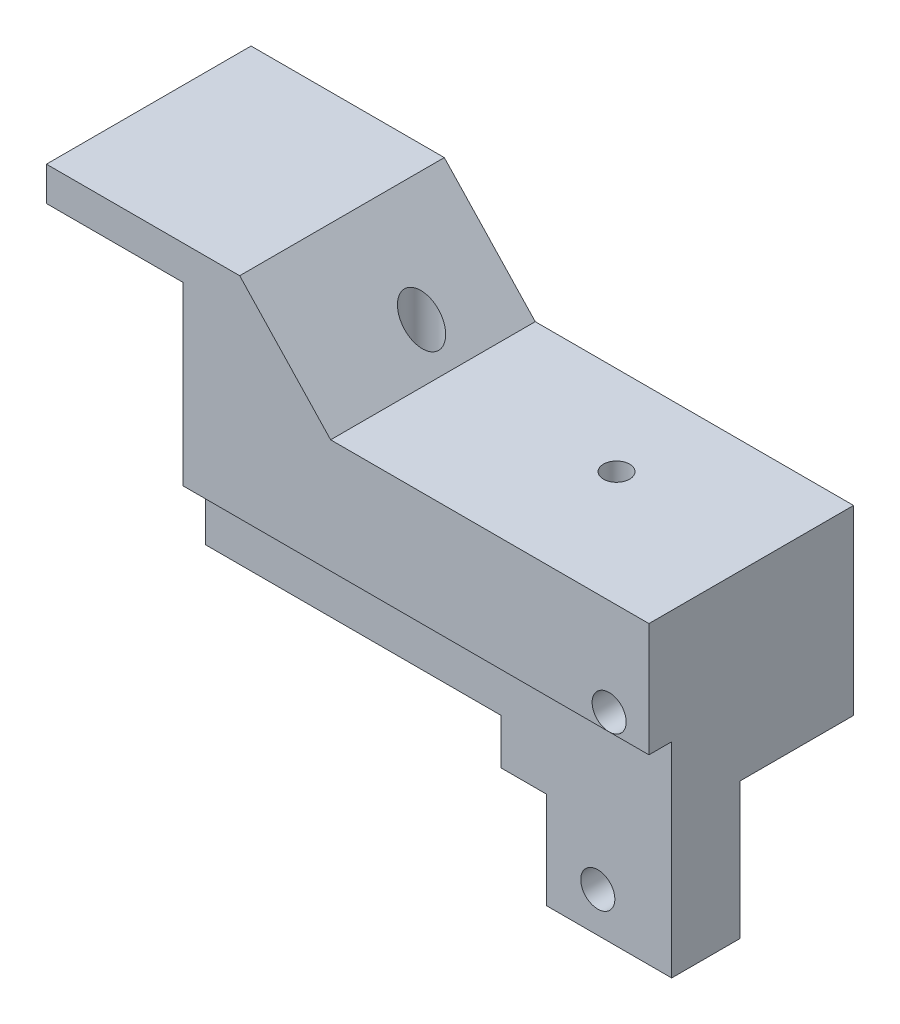
SolidWorks part; units mm, degrees
ref_plane "Front Plane" through (0, 0, 0) normal (0, 0, 1) x (1, 0, 0)
ref_plane "Top Plane" through (0, 0, 0) normal (0, 1, 0) x (1, 0, 0)
ref_plane "Right Plane" through (0, 0, 0) normal (1, 0, 0) x (0, 0, -1)
sketch "Sketch1" plane through (0, 0, 0) normal (0, 0, 1) x (1, 0, 0)
  line L1 (-20.5, -14) -> (20.5, -14)
  line L2 (-20.5, -14) -> (-20.5, 14)
  line L3 (-20.5, 14) -> (20.5, 14)
  line L4 (20.5, -14) -> (20.5, 14)
  line L5 (-20.5, -14) -> (20.5, 14) construction
  line L6 (-20.5, 14) -> (20.5, -14) construction
  point P0 (0, 0)
  dimension "D1" = 41
  dimension "D2" = 28
extrude "Boss-Extrude1" add sketch "Sketch1" along normal blind 18
sketch "Sketch2" plane through (0, 0, 18) normal (0, 0, 1) x (1, 0, 0)
  line L0 (9.5, -14) -> (9.5, -5.5)
  line L1 (-20.5, -14) -> (20.5, -14) construction
  line L2 (9.5, -5.5) -> (5.5, -5.5)
  line L3 (5.5, -5.5) -> (5.5, -1.5)
  line L4 (5.5, -1.5) -> (-20.5, -1.5)
  line L5 (-20.5, 14) -> (-20.5, -14) construction
  line L6 (-20.5, -1.5) -> (-20.5, -14)
  line L7 (-20.5, -14) -> (9.5, -14)
  dimension "D1" = 11
  dimension "D2" = 8.5
  dimension "D3" = 4
extrude "Cut-Extrude1" cut sketch "Sketch2" against normal blind 18
sketch "Sketch3" plane through (0, 0, 18) normal (0, 0, 1) x (1, 0, 0)
  line L0 (-20.5, -1.5) -> (-20.5, 22.5) construction
  line L1 (-20.5, 22.5) -> (-32.5, 22.5)
  line L2 (-32.5, 22.5) -> (-32.5, 19.5)
  line L3 (-32.5, 19.5) -> (-20.5, 19.5)
  line L4 (-20.5, 19.5) -> (-20.5, 14)
  line L7 (20.5, 14) -> (-20.5, 14) construction
  line L8 (-7.5, 14) -> (-20.5, 14)
  line L9 (-20.5, 22.5) -> (-15.5, 22.5)
  line L10 (-15.5, 22.5) -> (-7.5, 14)
  dimension "D1" = 24
  dimension "D2" = 12
  dimension "D3" = 3
  dimension "D4" = 13
  dimension "D5" = 5
extrude "Boss-Extrude2" add sketch "Sketch3" against normal up to surface (18 mm away) up to face at (3.75, -1.75, 0)
sketch "Sketch4" plane through (0, 0, 18) normal (0, 0, 1) x (1, 0, 0)
  line L0 (20.5, -14) -> (20.5, 4)
  line L1 (20.5, -14) -> (20.5, 14) construction
  line L2 (20.5, 4) -> (-20.5, 4)
  line L3 (-20.5, 19.5) -> (-20.5, -1.5) construction
  line L4 (-20.5, 4) -> (-20.5, -14)
  line L5 (-20.5, -14) -> (20.5, -14)
  dimension "D1" = 18
extrude "Cut-Extrude2" cut sketch "Sketch4" against normal blind 2
sketch "Sketch5" plane through (0, 0, 18) normal (0, 0, 1) x (1, 0, 0)
  line L0 (20.5, 4) -> (-20.5, 4) construction
  line L1 (20.5, 4) -> (20.5, 14) construction
  circle A0 centre (17, 5.501) radius 1.5
  point P2 (0, 0)
  dimension "D1" = 3
  dimension "D2" = 1.501
  dimension "D3" = 3.5
extrude "Cut-Extrude9" cut sketch "Sketch5" against normal blind 11
sketch "Sketch6" plane through (0, 0, 16) normal (0, 0, 1) x (1, 0, 0)
  line L0 (9.5, -14) -> (20.5, -14) construction
  line L1 (9.5, -5.5) -> (9.5, -14) construction
  circle A0 centre (14, -10.5) radius 1.5
  dimension "D3" = 3
  dimension "D1" = 3.5
  dimension "D2" = 4.5
extrude "Cut-Extrude10" cut sketch "Sketch6" against normal through all
sketch "Sketch7" plane through (0, 0, 0) normal (0, 0, -1) x (-1, 0, 0)
  circle A0 centre (-17, 5.501) radius 2.5
  dimension "D1" = 5
extrude "Cut-Extrude11" cut sketch "Sketch7" against normal blind 7
sketch "Sketch8" plane through (0, 0, 0) normal (0, 0, -1) x (-1, 0, 0)
  line L0 (-9.5, -14) -> (-9.5, -2)
  line L1 (-9.5, -2) -> (-20.5, -2)
  line L2 (-20.5, -14) -> (-20.5, 14) construction
  line L3 (-20.5, -2) -> (-20.5, -14)
  line L4 (-20.5, -14) -> (-9.5, -14)
  dimension "D1" = 12
extrude "Cut-Extrude12" cut sketch "Sketch8" against normal blind 10
sketch "Sketch9" plane through (0, -1.5, 0) normal (0, -1, 0) x (1, 0, 0)
  line L0 (-20.5, 0) -> (-20.5, 18) construction
  line L1 (5.5, 0) -> (-20.5, 0) construction
  circle A0 centre (-10, 7.5) radius 5
  dimension "D1" = 10.5
  dimension "D2" = 10
  dimension "D3" = 7.5
extrude "Cut-Extrude13" cut sketch "Sketch9" against normal blind 4
sketch "Sketch10" plane through (0, 2.5, 0) normal (0, -1, 0) x (1, 0, 0)
  circle A0 centre (-10, 7.5) radius 1.5
  dimension "D1" = 3
extrude "Cut-Extrude14" cut sketch "Sketch10" against normal through all
sketch "Sketch11" plane through (0, -5.5, 0) normal (0, -1, 0) x (1, 0, 0)
  line L0 (20.5, 16) -> (-20.5, 16) construction
  circle A0 centre (7.5, 7.85) radius 1.15
  dimension "D2" = 8.15
  dimension "D1" = 2.3
extrude "Cut-Extrude15" cut sketch "Sketch11" against normal through all
